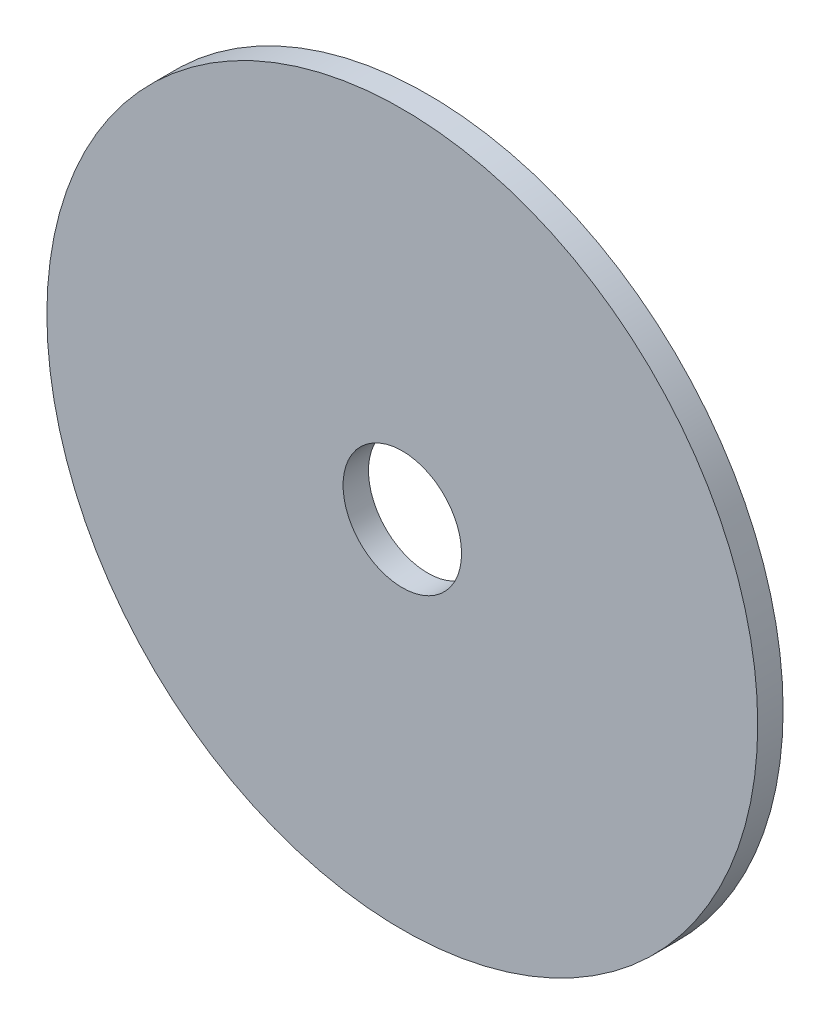
SolidWorks part; units mm, degrees
material "AISI 316 Chapa de acero inoxidable (SS)"
ref_plane "Alzado" through (0, 0, 0) normal (0, 0, 1) x (1, 0, 0)
ref_plane "Planta" through (0, 0, 0) normal (0, 1, 0) x (1, 0, 0)
ref_plane "Vista lateral" through (0, 0, 0) normal (1, 0, 0) x (0, 0, -1)
sketch "Croquis1" plane through (0, 0, 0) normal (1, 0, 0) x (0, 0, -1)
  line L0 (0, 0) -> (61.4836, 0) construction
  line L1 (0, 0) -> (0, 21)
  line L2 (0, 21) -> (1.5, 21)
  line L3 (1.5, 21) -> (1.5, 0)
  line L4 (1.5, 0) -> (0, 0)
  dimension "D1" = 1.5
  dimension "D2" = 42
revolve "Revolución1" add sketch "Croquis1" angle 360 about L0
sketch "Croquis2" plane through (0, 0, 0) normal (0, 0, 1) x (1, 0, 0)
  circle A0 centre (0, 0) radius 3.5
  dimension "D1" = 7
extrude "Cortar-Extruir1" cut sketch "Croquis2" against normal through all
